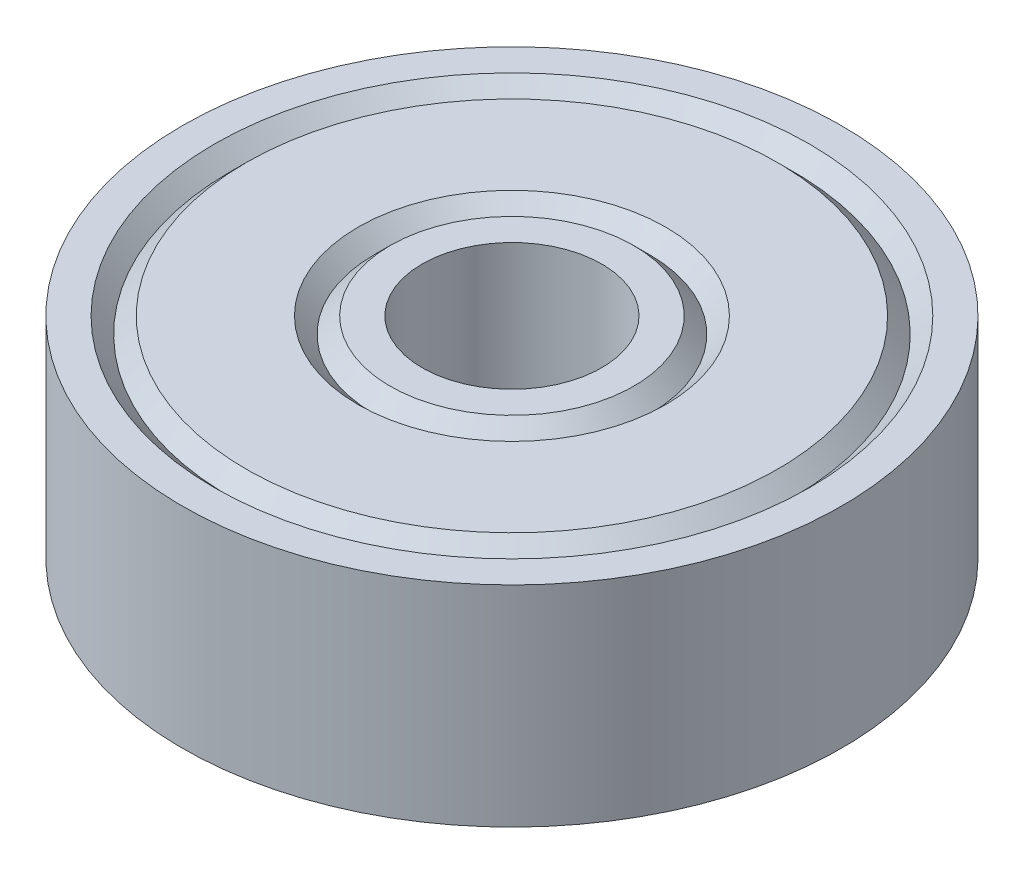
SolidWorks part; units mm, degrees
ref_plane "Front Plane" through (0, 0, 0) normal (0, 0, 1) x (1, 0, 0)
ref_plane "Top Plane" through (0, 0, 0) normal (0, 1, 0) x (1, 0, 0)
ref_plane "Right Plane" through (0, 0, 0) normal (1, 0, 0) x (0, 0, -1)
sketch "Sketch1" plane through (0, 0, 0) normal (0, 0, 1) x (1, 0, 0)
  line L0 (0, 3.5) -> (0, -3.5) construction
  line L1 (-3, 3.5) -> (-4.0667, 3.5)
  line L2 (-3, 3.5) -> (-3, -3.5)
  line L3 (-3, -3.5) -> (-4.0667, -3.5)
  line L4 (-11, 3.5) -> (-11, -3.5)
  line L5 (-9.9333, 3.5) -> (-9.4, 2.9667)
  line L6 (-9.4, 2.9667) -> (-8.8667, 3.5)
  line L7 (-5.1333, 3.5) -> (-4.6, 2.9667)
  line L8 (-4.6, 2.9667) -> (-4.0667, 3.5)
  line L9 (-9.9333, -3.5) -> (-9.4, -2.9667)
  line L10 (-9.4, -2.9667) -> (-8.8667, -3.5)
  line L11 (-5.1333, -3.5) -> (-4.6, -2.9667)
  line L12 (-4.6, -2.9667) -> (-4.0667, -3.5)
  line L13 (-5.1333, -3.5) -> (-8.8667, -3.5)
  line L14 (-9.9333, -3.5) -> (-11, -3.5)
  line L15 (-9.9333, 3.5) -> (-11, 3.5)
  line L16 (-5.1333, 3.5) -> (-8.8667, 3.5)
  line L17 (-9.4, 2.9667) -> (-4.6, 2.9667) construction
  line L18 (-9.4, 2.9667) -> (-9.4, -2.9667) construction
  line L19 (-4.6, -2.9667) -> (-9.4, -2.9667) construction
  line L20 (-4.6, 2.9667) -> (-4.6, -2.9667) construction
  line L21 (-9.4, 0) -> (-7.8, 0) construction
  line L22 (-4.0667, 3.5) -> (-5.1333, 3.5) construction
  line L23 (-7.8, 0) -> (-6.2, 0) construction
  line L24 (-9.4, 0) -> (-11, 0) construction
  line L25 (-6.2, 0) -> (-4.6, 0) construction
  line L26 (-4.6, 0) -> (-3, 0) construction
  dimension "D1" = 7
  dimension "D2" = 6
  dimension "D3" = 22
revolve "Revolve1" add sketch "Sketch1" angle 360 about L0
